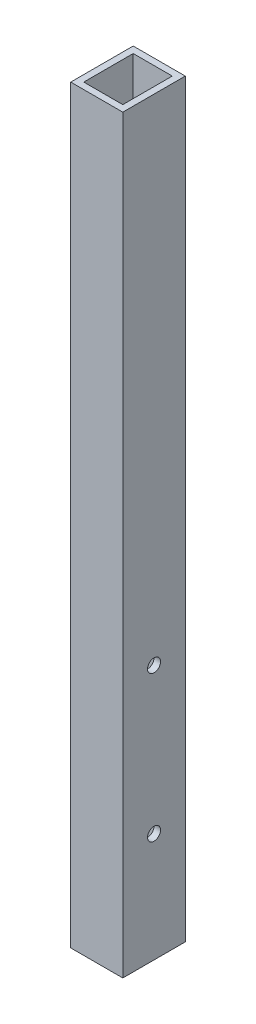
SolidWorks part; units mm, degrees
material "AISI 304"
ref_plane "Front Plane" through (0, 0, 0) normal (0, 0, 1) x (1, 0, 0)
ref_plane "Top Plane" through (0, 0, 0) normal (0, 1, 0) x (1, 0, 0)
ref_plane "Right Plane" through (0, 0, 0) normal (1, 0, 0) x (0, 0, -1)
sketch "Sketch1" plane through (0, 0, 0) normal (0, 1, 0) x (1, 0, 0)
  line L1 (-31.75, -38.1) -> (31.75, -38.1)
  line L2 (-31.75, -38.1) -> (-31.75, 38.1)
  line L3 (-31.75, 38.1) -> (31.75, 38.1)
  line L4 (31.75, -38.1) -> (31.75, 38.1)
  line L5 (-31.75, -38.1) -> (31.75, 38.1) construction
  line L6 (-31.75, 38.1) -> (31.75, -38.1) construction
  point P0 (0, 0)
  dimension "D1" = 76.2
  dimension "D2" = 63.5
extrude "Boss-Extrude1" add sketch "Sketch1" along normal blind 914.4
sketch "Sketch2" plane through (0, 914.4, 0) normal (0, 1, 0) x (1, 0, 0)
  line L0 (-31.75, 38.1) -> (-31.75, -38.1) construction
  line L1 (-23.8125, -30.1625) -> (23.8125, -30.1625)
  line L2 (-23.8125, -30.1625) -> (-23.8125, 30.1625)
  line L3 (-23.8125, 30.1625) -> (23.8125, 30.1625)
  line L4 (23.8125, -30.1625) -> (23.8125, 30.1625)
  line L5 (-23.8125, -30.1625) -> (23.8125, 30.1625) construction
  line L6 (-23.8125, 30.1625) -> (23.8125, -30.1625) construction
  line L7 (31.75, -38.1) -> (31.75, 38.1) construction
  line L8 (31.75, 38.1) -> (-31.75, 38.1) construction
  line L9 (-31.75, -38.1) -> (31.75, -38.1) construction
  point P0 (0, 0)
  dimension "D1" = 7.9375
  dimension "D2" = 7.9375
  dimension "D3" = 7.9375
  dimension "D4" = 7.9375
extrude "Cut-Extrude1" cut sketch "Sketch2" against normal through all
sketch "Sketch3" plane through (31.75, 0, 0) normal (1, 0, 0) x (0, 0, -1)
  line L0 (-91.3282, 393.7) -> (87.3355, 393.7) construction
  line L1 (-38.1, 914.4) -> (38.1, 914.4) construction
  circle A0 centre (0, 311.15) radius 7.9375
  circle A1 centre (0, 133.35) radius 7.9375
  dimension "D4" = 15.875
  dimension "D5" = 15.875
  dimension "D1" = 520.7
  dimension "D2" = 177.8
  dimension "D3" = 82.55
extrude "Cut-Extrude2" cut sketch "Sketch3" against normal through all
